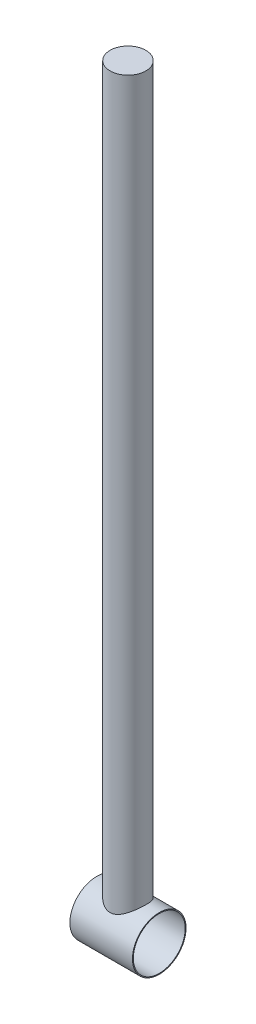
SolidWorks part; units mm, degrees
material "Chrome Stainless Steel"
ref_plane "Plano frontal" through (0, 0, 0) normal (0, 0, 1) x (1, 0, 0)
ref_plane "Plano superior" through (0, 0, 0) normal (0, 1, 0) x (1, 0, 0)
ref_plane "Plano direito" through (0, 0, 0) normal (1, 0, 0) x (0, 0, -1)
sketch "Sketch2" plane through (0, 0, 0) normal (1, 0, 0) x (0, 0, -1)
  circle A0 centre (0, 0) radius 30
  circle A1 centre (0, 0) radius 29
  dimension "D1" = 60
  dimension "D2" = 1
extrude "Boss-Extrude3" add sketch "Sketch2" along normal mid plane 70
sketch "Sketch1" plane through (0, 0, 0) normal (0, 1, 0) x (1, 0, 0)
  circle A0 centre (0, 0) radius 20
  dimension "D1" = 40
extrude "Boss-Extrude4" add sketch "Sketch1" against normal up to surface (815.6393 mm away) from offset 838
